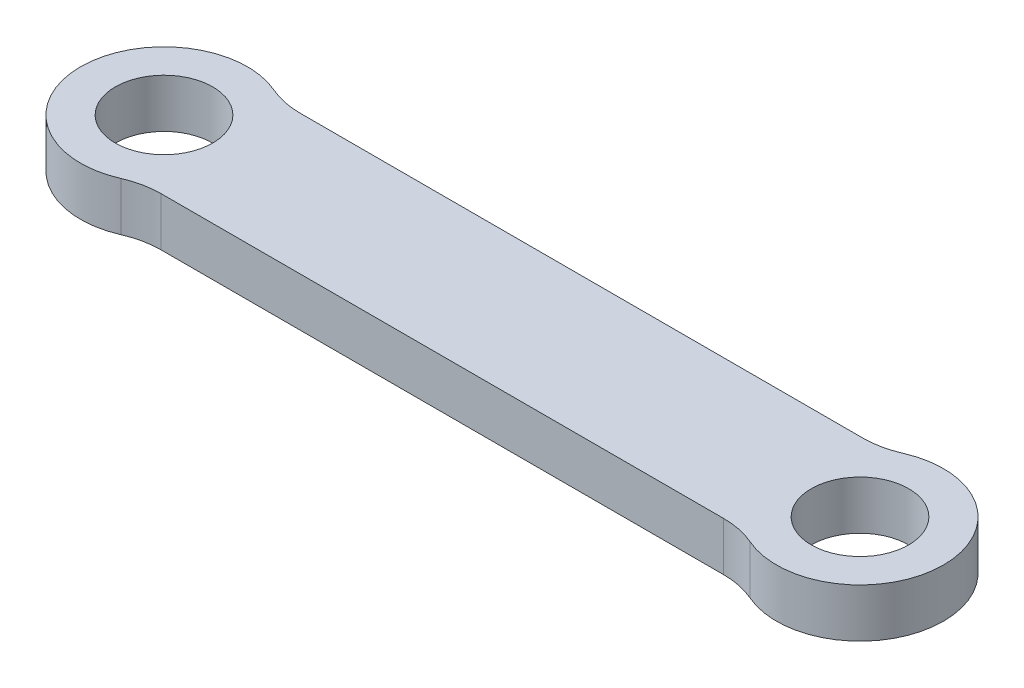
SolidWorks part; units mm, degrees
ref_plane "Front Plane" through (0, 0, 0) normal (0, 0, 1) x (1, 0, 0)
ref_plane "Top Plane" through (0, 0, 0) normal (0, 1, 0) x (1, 0, 0)
ref_plane "Right Plane" through (0, 0, 0) normal (1, 0, 0) x (0, 0, -1)
sketch "Sketch1" plane through (0, 0, 0) normal (0, 1, 0) x (1, 0, 0)
  line L0 (0, 0) -> (25, 0) construction
  line L1 (1.6583, 2.5) -> (23.3417, 2.5)
  line L2 (1.6583, -2.5) -> (23.3417, -2.5)
  circle A0 centre (0, 0) radius 3
  circle A1 centre (25, 0) radius 3
  circle A2 centre (0, 0) radius 1.75
  circle A3 centre (25, 0) radius 1.75
  dimension "D1" = 6
  dimension "D3" = 6
  dimension "D5" = 3.5
  dimension "D6" = 3.5
  dimension "D2" = 25
  dimension "D4" = 2.5
extrude "Boss-Extrude1" add sketch "Sketch1" along normal blind 1.75
fillet "Fillet1" radius 3 4 edges at (1.6583, 0.875, 2.5) (23.3417, 0.875, 2.5) (23.3417, 0.875, -2.5) (1.6583, 0.875, -2.5)
